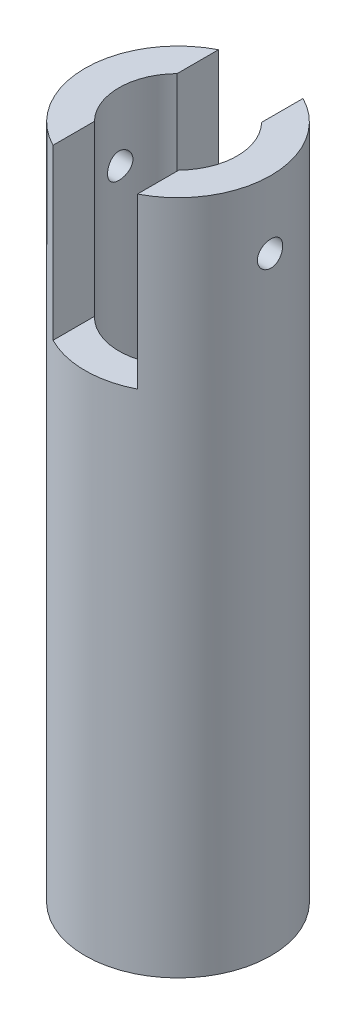
SolidWorks part; units mm, degrees
ref_plane "Front Plane" through (0, 0, 0) normal (0, 0, 1) x (1, 0, 0)
ref_plane "Top Plane" through (0, 0, 0) normal (0, 1, 0) x (1, 0, 0)
ref_plane "Right Plane" through (0, 0, 0) normal (1, 0, 0) x (0, 0, -1)
sketch "Sketch1" plane through (0, 0, 0) normal (0, 1, 0) x (1, 0, 0)
  circle A0 centre (0, 0) radius 5.5
  circle A1 centre (0, 0) radius 3.5
  dimension "D1" = 11
  dimension "D2" = 7
extrude "Boss-Extrude1" add sketch "Sketch1" along normal blind 40
sketch "Sketch2" plane through (0, 0, 0) normal (0, 0, 1) x (1, 0, 0)
  line L1 (-5.5, 40) -> (5.5, 40)
  line L2 (-5.5, 40) -> (-5.5, 0)
  line L3 (-5.5, 0) -> (5.5, 0)
  line L4 (5.5, 40) -> (5.5, 0)
  line L5 (-2.5, 50) -> (2.5, 50)
  line L6 (-2.5, 50) -> (-2.5, 30)
  line L7 (-2.5, 30) -> (2.5, 30)
  line L8 (2.5, 50) -> (2.5, 30)
  line L9 (-2.5, 50) -> (2.5, 30) construction
  line L10 (-2.5, 30) -> (2.5, 50) construction
  point P6 (0, 40)
  dimension "D1" = 10
  dimension "D2" = 5
extrude "Cut-Extrude1" cut sketch "Sketch2" against normal mid plane 40 contours L8 L1 L6 L7 | L8 L5 L6 L1
sketch "Sketch3" plane through (0, 0, 0) normal (1, 0, 0) x (0, 0, -1)
  line L0 (0, 30) -> (0, 36)
  line L2 (4.899, 40) -> (-4.899, 40) construction
  circle A0 centre (0, 36) radius 0.75
  dimension "D1" = 1.5
  dimension "D2" = 6
  dimension "D3" = 6
  dimension "D4" = 4
extrude "Cut-Extrude2" cut sketch "Sketch3" along normal mid plane 20 contours A0
